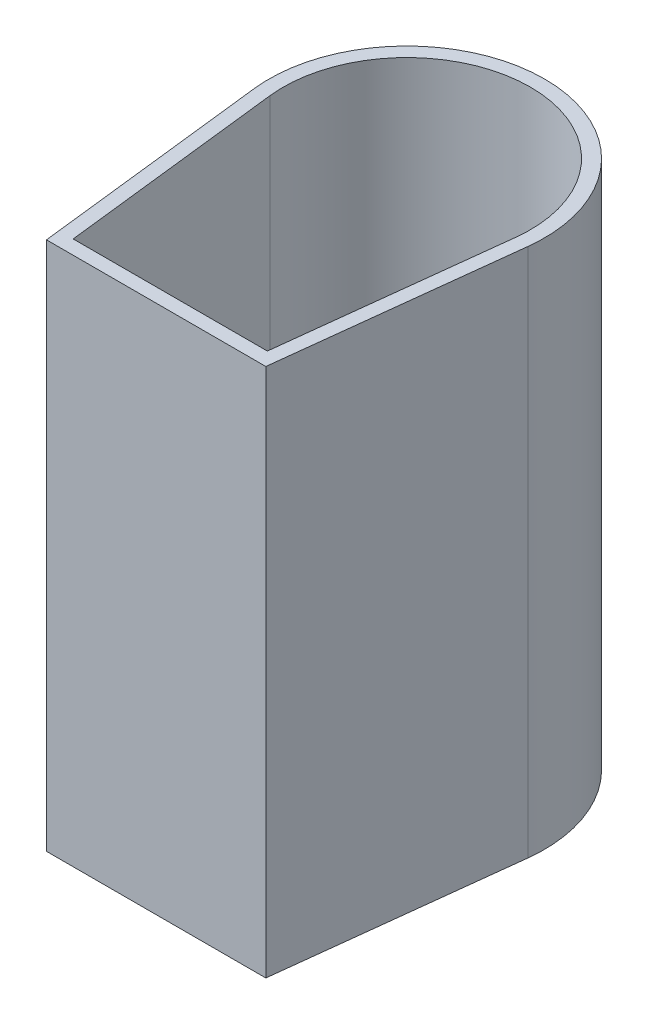
SolidWorks part; units mm, degrees
ref_plane "Front Plane" through (0, 0, 0) normal (0, 0, 1) x (1, 0, 0)
ref_plane "Top Plane" through (0, 0, 0) normal (0, 1, 0) x (1, 0, 0)
ref_plane "Right Plane" through (0, 0, 0) normal (1, 0, 0) x (0, 0, -1)
sketch "Sketch3" plane through (0, 0, 0) normal (0, 1, 0) x (1, 0, 0)
  line L0 (0, 0) -> (0, -67) construction
  line L1 (0, -67) -> (-27.5, -67)
  line L2 (-27.5, -67) -> (-34.7692, -4.0126)
  line L3 (0, -67) -> (27.5, -67)
  line L4 (27.5, -67) -> (34.7692, -4.0126)
  line L5 (-31.0649, -71) -> (-38.7428, -4.4712)
  line L6 (0, -71) -> (-31.0649, -71)
  line L7 (0, -71) -> (31.0649, -71)
  line L8 (31.0649, -71) -> (38.7428, -4.4712)
  arc A0 (34.7692, -4.0126) -> (-34.7692, -4.0126) centre (0, 0) ccw
  arc A1 (38.7428, -4.4712) -> (-38.7428, -4.4712) centre (0, 0) ccw
  dimension "D1" = 70
  dimension "D2" = 67
  dimension "D3" = 27.5
  dimension "D4" = 27.5
  dimension "D5" = 4
extrude "Boss-Extrude1" add sketch "Sketch3" along normal blind 150
sketch "Sketch4" plane through (0, 0, 0) normal (0, -1, 0) x (1, 0, 0)
  line L0 (-27.5, 67) -> (-34.7692, 4.0126)
  line L1 (34.7692, 4.0126) -> (27.5, 67)
  line L2 (-27.5, 67) -> (27.5, 67)
  arc A0 (-34.7692, 4.0126) -> (34.7692, 4.0126) centre (0, 0) ccw
  dimension "D1" = 70
extrude "Boss-Extrude2" add sketch "Sketch4" against normal blind 5
sketch "Sketch6" plane through (0, 0, 0) normal (0, -1, 0) x (1, 0, 0)
  circle A0 centre (0, 0) radius 6.25
  dimension "D1" = 12.5
extrude "Cut-Extrude2" cut sketch "Sketch6" against normal up to next
sketch "Sketch7" plane through (0, 0, 0) normal (0, -1, 0) x (1, 0, 0)
  line L0 (0, 0) -> (24, 0) construction
  line L1 (0, 0) -> (0, 6.25) construction
  circle A0 centre (24, 0) radius 3.25
  circle A1 centre (0, 0) radius 6.25 construction
  circle A2 centre (-24, 0) radius 3.25
  dimension "D2" = 6.5
  dimension "D1" = 24
extrude "Cut-Extrude3" cut sketch "Sketch7" against normal up to next
